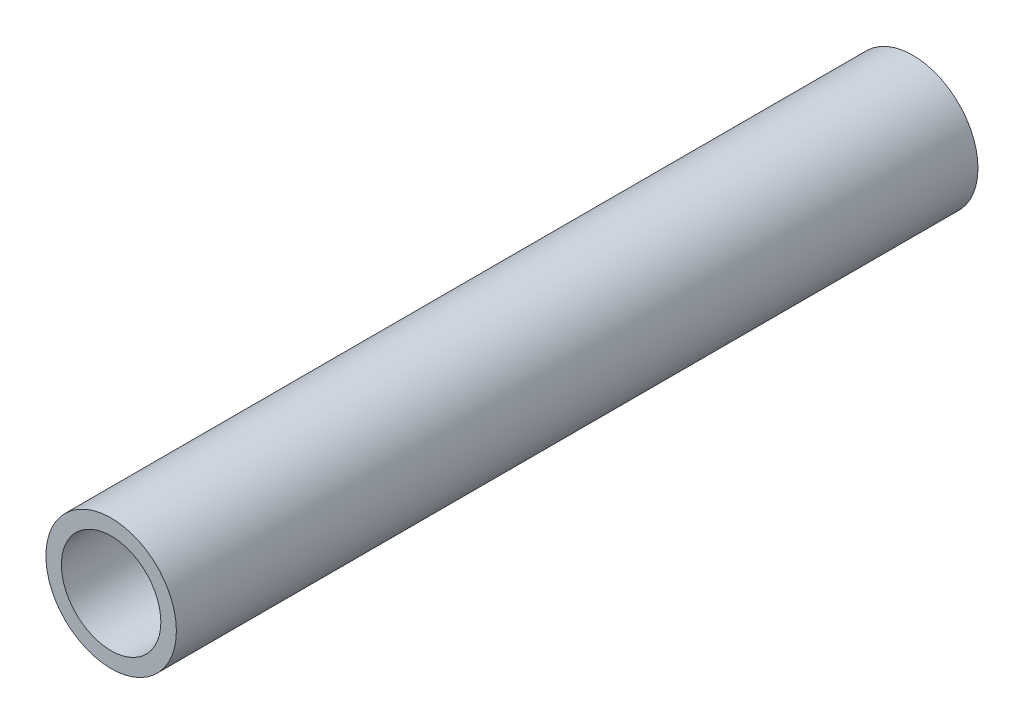
SolidWorks part; units mm, degrees
material "橡胶"
ref_plane "前视基准面" through (0, 0, 0) normal (0, 0, 1) x (1, 0, 0)
ref_plane "上视基准面" through (0, 0, 0) normal (0, 1, 0) x (1, 0, 0)
ref_plane "右视基准面" through (0, 0, 0) normal (1, 0, 0) x (0, 0, -1)
sketch "草图1" plane through (0, 0, 0) normal (0, 0, 1) x (1, 0, 0)
  circle A0 centre (0, 0) radius 5.25
  circle A1 centre (0, 0) radius 4
  dimension "D1" = 8
  dimension "D2" = 10.5
extrude "拉伸1" add sketch "草图1" along normal mid plane 64.5
